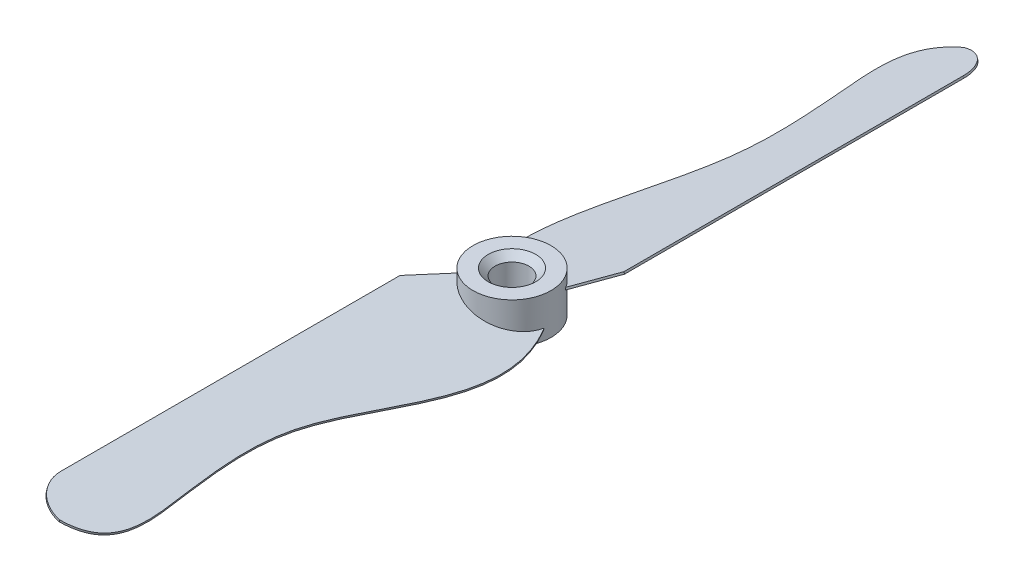
SolidWorks part; units mm, degrees
ref_plane "Front Plane" through (0, 0, 0) normal (0, 0, 1) x (1, 0, 0)
ref_plane "Top Plane" through (0, 0, 0) normal (0, 1, 0) x (1, 0, 0)
ref_plane "Right Plane" through (0, 0, 0) normal (1, 0, 0) x (0, 0, -1)
sketch "Sketch1" plane through (0, 0, 0) normal (0, 1, 0) x (1, 0, 0)
  circle A0 centre (0, 0) radius 5.75
  dimension "D1" = 11.5
extrude "Boss-Extrude1" add sketch "Sketch1" along normal mid plane 6
sketch "Sketch2" plane through (0, 0, 0) normal (0, 0, 1) x (1, 0, 0)
  line L0 (-5.75, 1.5407) -> (5.8818, -1.576) construction
  line L1 (-5.75, 3) -> (-5.75, -3) construction
  line L2 (-5.75, -3) -> (5.75, -3) construction
  dimension "D1" = 15
ref_plane "Plane1" through (0, 0, 0) normal (-0.2588, -0.9659, 0) x (0.9659, -0.2588, 0)
sketch "Sketch3" plane through (0, 0, 0) normal (-0.2588, -0.9659, 0) x (0.9659, -0.2588, 0)
  line L0 (-4.8399, 2.6237) -> (-8.3349, 8.5)
  line L1 (-8.3349, 8.5) -> (-8.3349, 58.5)
  line L2 (10.2032, 63.5) -> (-3.3349, 63.5) construction
  arc A0 (-8.3349, 58.5) -> (-3.3349, 63.5) centre (-3.3349, 58.5) cw
  spline S0 degree 3 poles (-4.8399, 2.6237) (-4.0997, 4.0299) (-0.025, 7.4943) (5.2162, 3.5832) (5.747, 0.762) knots 0 0 0 0 0.356038 1 1 1 1
  spline S1 degree 3 poles (5.747, 0.762) (12.1314, 11.85) (-0.9362, 28.084) (1.4619, 49.5361) (2.9061, 61.806) (-3.3349, 63.5) knots 0 0 0 0 0.512789 0.775226 1 1 1 1
  dimension "D3" = 5
  dimension "D1" = 63.5
  dimension "D2" = 55
extrude "Boss-Extrude2" add sketch "Sketch3" along normal mid plane 0.3
pattern_circular "CirPattern1" count 2 over 360 about axis through (0, 3, 0) along (0, -1, 0) of "Boss-Extrude2"
sketch "Sketch4" plane through (0, -3, 0) normal (0, -1, 0) x (1, 0, 0)
  circle A0 centre (0, 0) radius 2.5
  dimension "D1" = 5
extrude "Cut-Extrude1" cut sketch "Sketch4" against normal through all
chamfer "Chamfer1" distance 1 angle 45 2 edges at (0, -3, -2.5) (0, 3, -2.5)
scale "Scale1" scale about centroid uniform scaling yes scale factor 0.8
